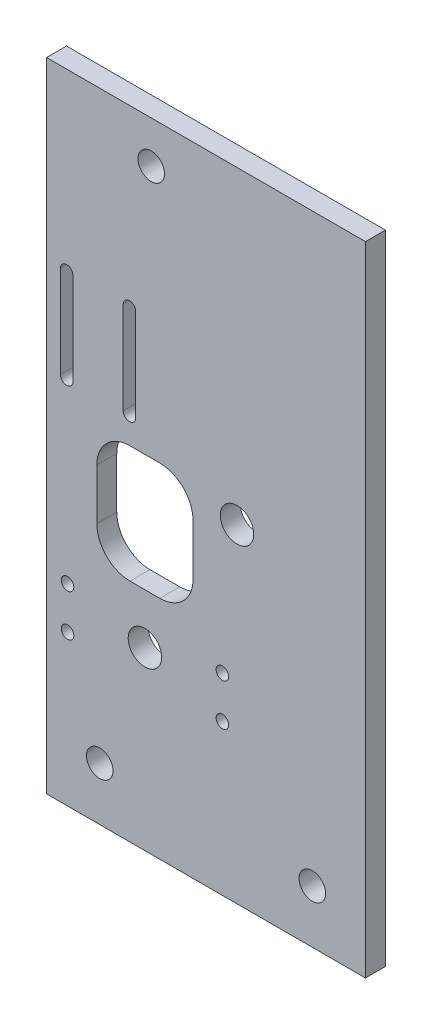
SolidWorks part; units mm, degrees
ref_plane "Front Plane" through (0, 0, 0) normal (0, 0, 1) x (1, 0, 0)
ref_plane "Top Plane" through (0, 0, 0) normal (0, 1, 0) x (1, 0, 0)
ref_plane "Right Plane" through (0, 0, 0) normal (1, 0, 0) x (0, 0, -1)
sketch "Sketch1" plane through (0, 0, 0) normal (0, 1, 0) x (1, 0, 0)
  line L1 (0, 0) -> (76.2, 0)
  line L2 (0, 0) -> (0, 4.7625)
  line L3 (0, 4.7625) -> (76.2, 4.7625)
  line L4 (76.2, 0) -> (76.2, 4.7625)
  dimension "D1" = 76.2
  dimension "D2" = 4.7625
extrude "Boss-Extrude1" add sketch "Sketch1" along normal blind 152.4
sketch "Sketch2" plane through (0, 0, 0) normal (0, 0, 1) x (1, 0, 0)
  line L0 (76.2, 152.4) -> (76.2, 0) construction
  line L1 (45.5, 78.4517) -> (23.5, 65.75) construction
  line L2 (0, 0) -> (76.2, 0) construction
  line L3 (23.5, 54.75) -> (23.5, 53) construction
  line L4 (23.5, 65.75) -> (76.2, 65.75) construction
  line L5 (0, 152.4) -> (0, 0) construction
  circle A0 centre (23.5, 42) radius 4
  circle A1 centre (45.5, 78.4517) radius 4
  circle A2 centre (23.5, 42) radius 11 construction
  circle A3 centre (23.5, 65.75) radius 11 construction
  dimension "D4" = 8
  dimension "D5" = 30
  dimension "D6" = 22
  dimension "D1" = 23.5
  dimension "D2" = 22
  dimension "D3" = 42
  dimension "D7" = 1.75
extrude "Cut-Extrude1" cut sketch "Sketch2" against normal through all
sketch "Sketch3" plane through (0, 0, 0) normal (0, 0, 1) x (1, 0, 0)
  line L1 (12, 54) -> (35, 54)
  line L2 (12, 54) -> (12, 82)
  line L3 (12, 82) -> (35, 82)
  line L4 (35, 54) -> (35, 82)
  circle A1 centre (23.5, 42) radius 4 construction
  circle A2 centre (45.5, 78.4517) radius 4 construction
  dimension "D2" = 33.5
  dimension "D1" = 8
  dimension "D3" = 23
  dimension "D4" = 28
extrude "Cut-Extrude2" cut sketch "Sketch3" against normal through all
fillet "Fillet1" radius 7.9375 4 edges at (12, 82, -2.3813) (35, 82, -2.3813) (35, 54, -2.3813) (12, 54, -2.3813)
sketch "Sketch4" plane through (0, 0, 0) normal (0, 0, 1) x (1, 0, 0)
  line L0 (4.8, 110.4517) -> (4.8, 88.4517) construction
  line L1 (6.3, 110.4517) -> (6.3, 88.4517)
  line L2 (3.3, 110.4517) -> (3.3, 88.4517)
  line L3 (19.8, 110.4517) -> (19.8, 88.4517) construction
  line L4 (21.3, 110.4517) -> (21.3, 88.4517)
  line L5 (18.3, 110.4517) -> (18.3, 88.4517)
  circle A2 centre (45.5, 78.4517) radius 4 construction
  arc A3 (6.3, 110.4517) -> (3.3, 110.4517) centre (4.8, 110.4517) ccw
  arc A4 (3.3, 88.4517) -> (6.3, 88.4517) centre (4.8, 88.4517) ccw
  arc A5 (21.3, 110.4517) -> (18.3, 110.4517) centre (19.8, 110.4517) ccw
  arc A6 (18.3, 88.4517) -> (21.3, 88.4517) centre (19.8, 88.4517) ccw
  point P6 (4.8, 99.4517)
  point P12 (19.8, 99.4517)
  dimension "D1" = 1.5
  dimension "D4" = 25.7
  dimension "D5" = 22
  dimension "D2" = 15
  dimension "D3" = 32
extrude "Cut-Extrude3" cut sketch "Sketch4" against normal through all
sketch "Sketch5" plane through (0, 0, 0) normal (0, 0, 1) x (1, 0, 0)
  line L0 (5, 36) -> (42, 36) construction
  line L1 (23.5, 36) -> (23.5, 42) construction
  line L2 (0, 152.4) -> (0, 0) construction
  circle A0 centre (5, 36) radius 1.5
  circle A1 centre (42, 36) radius 1.5
  circle A3 centre (5, 46) radius 1.5
  circle A4 centre (42, 46) radius 1.5
  circle A5 centre (23.5, 42) radius 11 construction
  point P14 (23.5, 53)
  dimension "D1" = 3
  dimension "D3" = 22
  dimension "D5" = 7
  dimension "D2" = 5
  dimension "D4" = 10
extrude "Cut-Extrude4" cut sketch "Sketch5" against normal through all
sketch "Sketch6" plane through (0, 0, 0) normal (0, 0, 1) x (1, 0, 0)
  line L1 (76.2, 152.4) -> (76.2, 0) construction
  line L2 (63.5, 0) -> (63.5, 12.7) construction
  line L3 (0, 0) -> (76.2, 0) construction
  line L4 (63.5, 12.7) -> (76.2, 12.7) construction
  line L5 (0, 12.7) -> (12.7, 12.7) construction
  line L6 (0, 152.4) -> (0, 0) construction
  circle A0 centre (12.7, 12.7) radius 3.175
  circle A1 centre (63.5, 12.7) radius 3.175
  dimension "D1" = 6.35
  dimension "D4" = 12.7
extrude "Cut-Extrude5" cut sketch "Sketch6" against normal through all
sketch "Sketch7" plane through (0, 0, 0) normal (0, 0, 1) x (1, 0, 0)
  line L1 (0, 0) -> (76.2, 0) construction
  line L3 (0, 152.4) -> (0, 0) construction
  circle A0 centre (25, 142.4) radius 3.175
  dimension "D1" = 6.35
  dimension "D2" = 142.4
  dimension "D3" = 25
extrude "Cut-Extrude6" cut sketch "Sketch7" against normal through all
